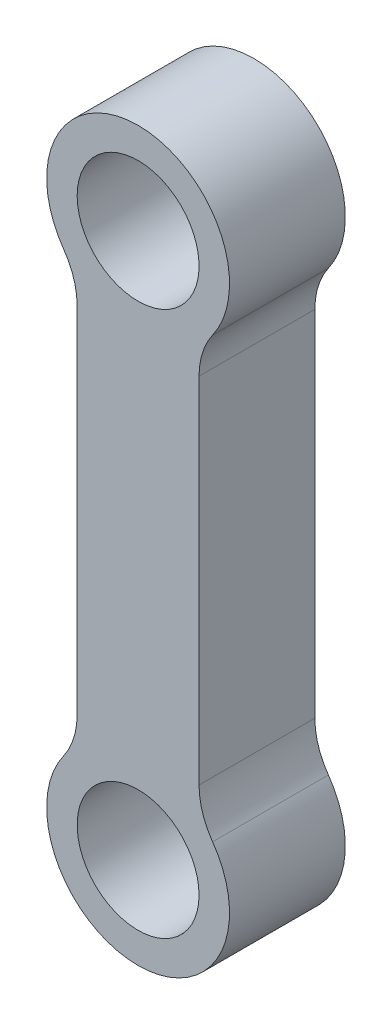
SolidWorks part; units mm, degrees
ref_plane "Plano frontal" through (0, 0, 0) normal (0, 0, 1) x (1, 0, 0)
ref_plane "Plano superior" through (0, 0, 0) normal (0, 1, 0) x (1, 0, 0)
ref_plane "Plano direito" through (0, 0, 0) normal (1, 0, 0) x (0, 0, -1)
sketch "Esboço1" plane through (0, 0, 0) normal (0, 0, 1) x (1, 0, 0)
  line L0 (-5, 14.5238) -> (-5, -14.5238)
  line L1 (0, 0) -> (-5, 0) construction
  line L4 (5, -14.5238) -> (5, 14.5238)
  circle A1 centre (0, -22.35) radius 5
  arc A2 (-6.1111, -18.0021) -> (6.1111, -18.0021) centre (0, -22.35) ccw
  arc A3 (6.1111, -18.0021) -> (5, -14.5238) centre (11, -14.5238) cw
  arc A4 (-6.1111, -18.0021) -> (-5, -14.5238) centre (-11, -14.5238) ccw
  arc A5 (6.1111, 18.0021) -> (5, 14.5238) centre (11, 14.5238) ccw
  arc A6 (-6.1111, 18.0021) -> (-5, 14.5238) centre (-11, 14.5238) cw
  circle A7 centre (0, 22.35) radius 5
  arc A8 (-6.1111, 18.0021) -> (6.1111, 18.0021) centre (0, 22.35) cw
  point P6 (-5, 13.7875)
  point P21 (-5, 14.5238)
  point P22 (5, 13.7875)
  dimension "D1" = 10
  dimension "D4" = 7.5
  dimension "D5" = 6
  dimension "D2" = 10
  dimension "D3" = 5
  dimension "D6" = 44.7
extrude "Ressalto-extrusão1" add sketch "Esboço1" along normal blind 9.5
